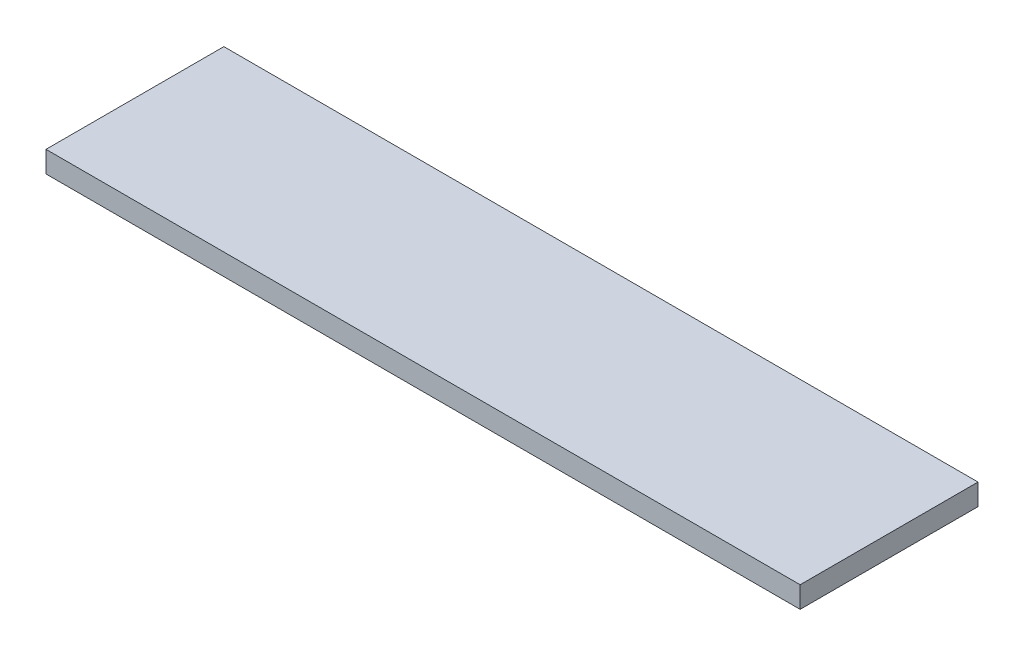
SolidWorks part; units mm, degrees
material "Pine"
ref_plane "Front Plane" through (0, 0, 0) normal (0, 0, 1) x (1, 0, 0)
ref_plane "Top Plane" through (0, 0, 0) normal (0, 1, 0) x (1, 0, 0)
ref_plane "Right Plane" through (0, 0, 0) normal (1, 0, 0) x (0, 0, -1)
sketch "Sketch1" plane through (0, 0, 0) normal (0, 1, 0) x (1, 0, 0)
  line L1 (0, 0) -> (212, 0)
  line L2 (0, 0) -> (0, 50)
  line L3 (0, 50) -> (212, 50)
  line L4 (212, 0) -> (212, 50)
  dimension "D1" = 212
  dimension "D2" = 50
extrude "Boss-Extrude1" add sketch "Sketch1" along normal blind 6
equation "\"BoardThickness\"= 6"
equation "\"D1@Boss-Extrude1\"=\"BoardThickness\""
equation "\"D1@Sketch1\"=200+\"BoardThickness\"*2"
